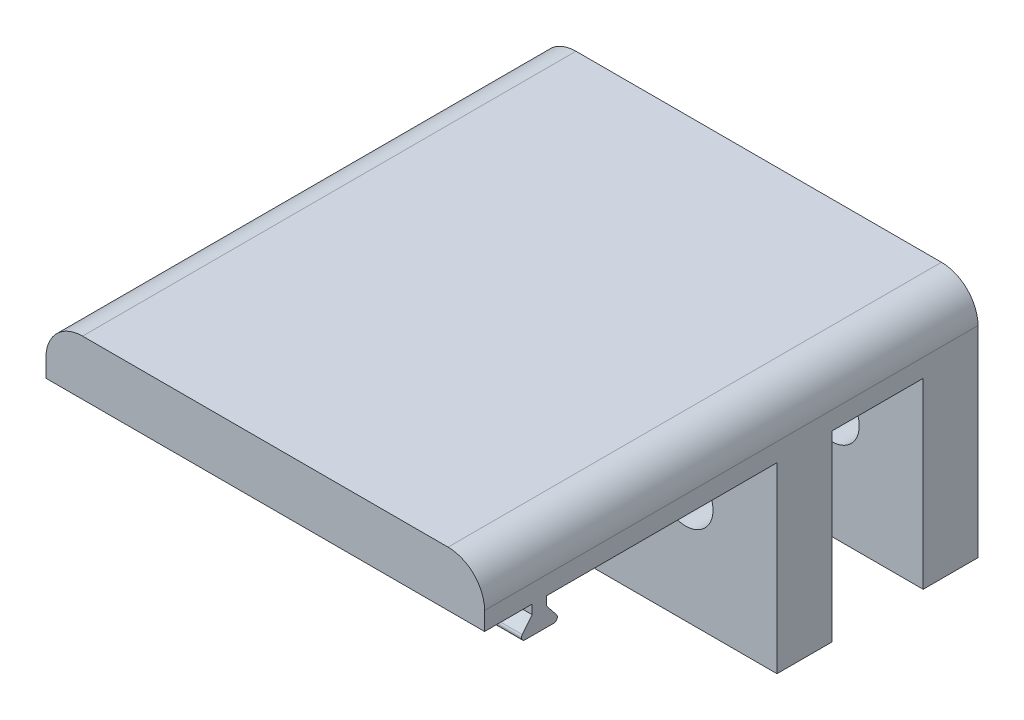
SolidWorks part; units mm, degrees
material "PET"
ref_plane "前视基准面" through (0, 0, 0) normal (0, 0, 1) x (1, 0, 0)
ref_plane "上视基准面" through (0, 0, 0) normal (0, 1, 0) x (1, 0, 0)
ref_plane "右视基准面" through (0, 0, 0) normal (1, 0, 0) x (0, 0, -1)
sketch "草图1" plane through (0, 0, 0) normal (0, 0, 1) x (1, 0, 0)
  line L0 (0, -1000) -> (0, 49000) construction
  line L1 (-12, -5) -> (12, -5)
  line L2 (-12, -5) -> (-12, 5)
  line L3 (-12, 5) -> (12, 5)
  line L4 (12, -5) -> (12, 5)
  line L5 (-12, -5) -> (12, 5) construction
  line L6 (-12, 5) -> (12, -5) construction
  circle A0 centre (-7, 1) radius 1.5
  circle A1 centre (7, 1) radius 1.5
  point P0 (0, 0)
  dimension "D3" = 3
  dimension "D1" = 24
  dimension "D2" = 10
  dimension "D4" = 4
  dimension "D5" = 7
extrude "凸台-拉伸1" add sketch "草图1" along normal blind 3 from offset 2.5
sketch "草图2" plane through (0, 0, 0) normal (0, 0, 1) x (1, 0, 0)
  line L4 (12, -5) -> (12, 5)
  line L5 (12, 5) -> (-12, 5)
  line L6 (-12, 5) -> (-12, -5)
  line L7 (-12, -5) -> (12, -5)
  line L8 (12, -5) -> (12, 5)
  line L9 (12, 5) -> (-12, 5)
  line L10 (-12, 5) -> (-12, -5)
  line L11 (-12, -5) -> (12, -5)
  circle A0 centre (7, 1) radius 1.5 construction
  circle A1 centre (-7, 1) radius 1.5 construction
  circle A2 centre (7, 1) radius 1.5
  circle A3 centre (-7, 1) radius 1.5
  dimension "D1" = 0
extrude "凸台-拉伸2" add sketch "草图2" against normal blind 3 from offset 2.5 separate body offset against normal yes
sketch "草图3" plane through (0, 5, 0) normal (0, 1, 0) x (1, 0, 0)
  line L1 (-12, 5.5) -> (12, 5.5)
  line L2 (-12, 5.5) -> (-12, -5.5)
  line L3 (-12, -5.5) -> (12, -5.5)
  line L4 (12, 5.5) -> (12, -5.5)
extrude "凸台-拉伸3" add sketch "草图3" along normal blind 3
sketch "草图4" plane through (0, 0, 5.5) normal (0, 0, 1) x (1, 0, 0)
  line L0 (12, -5) -> (12, 8) construction
  line L1 (-12, 8) -> (12, 8)
  line L2 (-12, 8) -> (-12, 5)
  line L3 (-12, 5) -> (12, 5)
  line L4 (12, 8) -> (12, 5)
  dimension "D1" = 3
extrude "凸台-拉伸4" add sketch "草图4" along normal blind 16
sketch "草图5" plane through (12, 0, 0) normal (1, 0, 0) x (0, 0, -1)
  line L0 (-15.5, 8) -> (-15.5, 5) construction
  line L1 (-21.5, 8) -> (5.5, 8) construction
  line L2 (-21.5, 5) -> (-5.5, 5) construction
  line L3 (-21.5, 5) -> (-21.5, 8) construction
  line L4 (-18.5, 5) -> (-19.7, 3.5)
  line L5 (-19.7, 3.5) -> (-17.3, 3.5)
  line L6 (-18.5, 5) -> (-18.5, 8) construction
  line L7 (-18.5, 5) -> (-17.3, 3.5)
  line L8 (-18.9, 5) -> (-18.9, 4.5)
  line L9 (-18.1, 5) -> (-18.1, 4.5)
  line L10 (-18.9, 5) -> (-18.1, 5)
  point P15 (-18.5, 3.5)
  line M14 (-21.5, 5) -> (-5.5, 5)
  dimension "D1" = 6
  dimension "D2" = 3
  dimension "D3" = 1.5
  dimension "D4" = 1.2
  dimension "D5" = 0.5
extrude "凸台-拉伸5" add sketch "草图5" against normal blind 24 contours L7 L4 L5 | L8 L4 M14 | L9 L7 M14
fillet "圆角1" radius 0.2 2 edges at (0, 3.5, 17.3) (0, 3.5, 19.7)
fillet "圆角2" radius 2 2 edges at (12, 8, 8) (-12, 8, 8)
